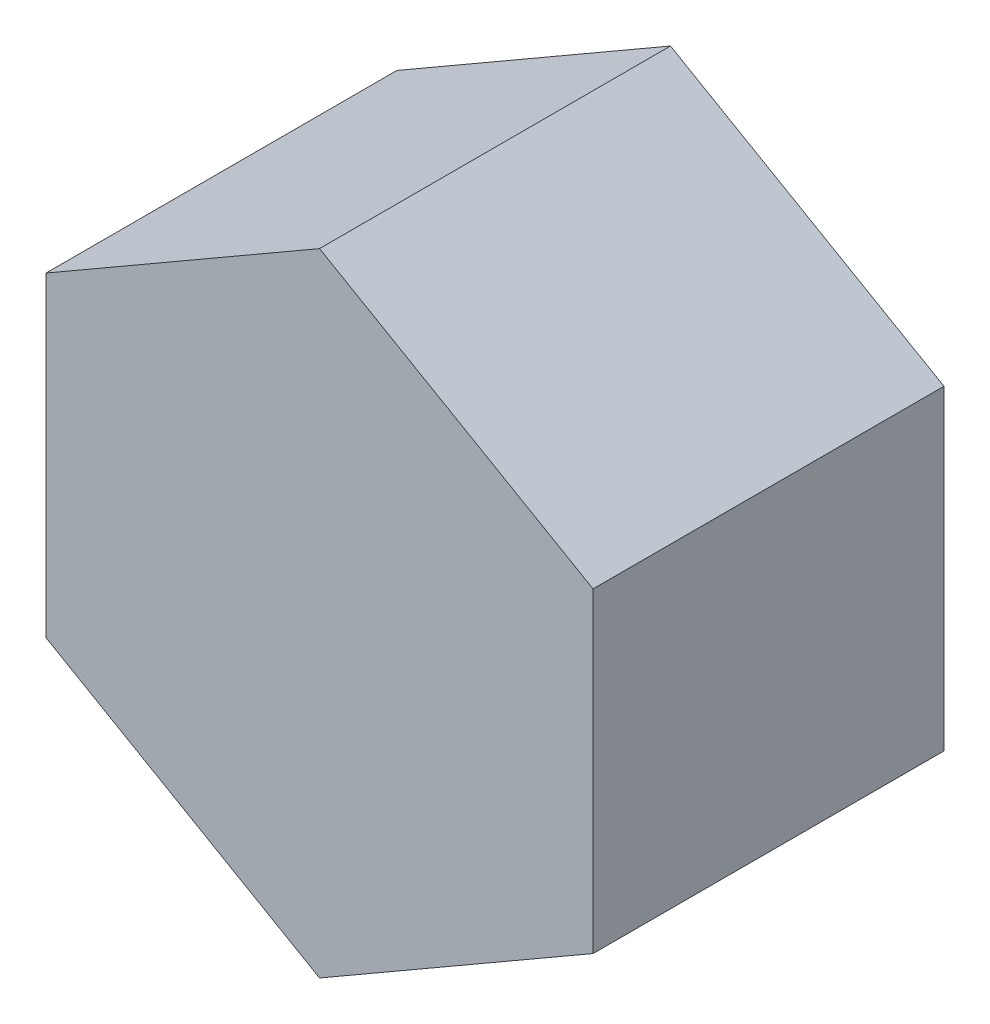
SolidWorks part; units mm, degrees
ref_plane "Front Plane" through (0, 0, 0) normal (0, 0, 1) x (1, 0, 0)
ref_plane "Top Plane" through (0, 0, 0) normal (0, 1, 0) x (1, 0, 0)
ref_plane "Right Plane" through (0, 0, 0) normal (1, 0, 0) x (0, 0, -1)
sketch "Sketch1" plane through (0, 0, 0) normal (0, 0, 1) x (1, 0, 0)
  line L1 (-1.7194, -3.0777) -> (-1.7194, -1.6343)
  line L2 (-1.7194, -1.6343) -> (-2.9694, -0.9126)
  line L3 (-2.9694, -0.9126) -> (-4.2194, -1.6343)
  line L4 (-4.2194, -1.6343) -> (-4.2194, -3.0777)
  line L5 (-4.2194, -3.0777) -> (-2.9694, -3.7994)
  line L6 (-2.9694, -3.7994) -> (-1.7194, -3.0777)
  circle A0 centre (-2.9694, -2.356) radius 1.25 construction
  circle A1 centre (-2.9694, -2.356) radius 2.75 construction
  circle A3 centre (-2.9694, -2.356) radius 1.4434 construction
  point P12 (-2.9694, -2.356)
extrude "Boss-Extrude1" add sketch "Sketch1" along normal blind 1 contours L4 L5 L6 L1 L2 L3
sketch "Sketch2" plane through (0, 0, 1) normal (0, 0, 1) x (1, 0, 0)
  line L0 (-2.9694, -0.9126) -> (-2.9694, -3.7994) construction
  line L2 (-2.9694, -6.856) -> (0.9277, -4.606)
  line L3 (0.9277, -4.606) -> (0.9277, -0.106)
  line L4 (0.9277, -0.106) -> (-2.9694, 2.144)
  line L5 (-2.9694, 2.144) -> (-6.8666, -0.106)
  line L6 (-6.8666, -0.106) -> (-6.8666, -4.606)
  line L7 (-6.8666, -4.606) -> (-2.9694, -6.856)
  circle A0 centre (-2.9694, -2.356) radius 2.775
  circle A1 centre (-2.9694, -2.356) radius 4.5 construction
  circle A2 centre (-2.9694, -2.356) radius 3.8971 construction
  dimension "D1" = 5.55
  dimension "D2" = 9
extrude "Boss-Extrude2" add sketch "Sketch2" against normal blind 3 separate body
sketch "Sketch3" plane through (0, 0, 1) normal (0, 0, 1) x (1, 0, 0)
  line L0 (0.9277, -4.606) -> (0.9277, -0.106) construction
  line L1 (-2.9694, -6.856) -> (0.9277, -4.606)
  line L2 (0.9277, -4.606) -> (0.9277, -0.106)
  line L3 (0.9277, -0.106) -> (-2.9694, 2.144)
  line L4 (-2.9694, 2.144) -> (-6.8666, -0.106)
  line L5 (-6.8666, -0.106) -> (-6.8666, -4.606)
  line L6 (-6.8666, -4.606) -> (-2.9694, -6.856)
  circle A0 centre (-2.9694, -2.356) radius 3.8971 construction
  circle A1 centre (-2.9694, -2.356) radius 4.5 construction
extrude "Boss-Extrude3" add sketch "Sketch3" along normal blind 2
